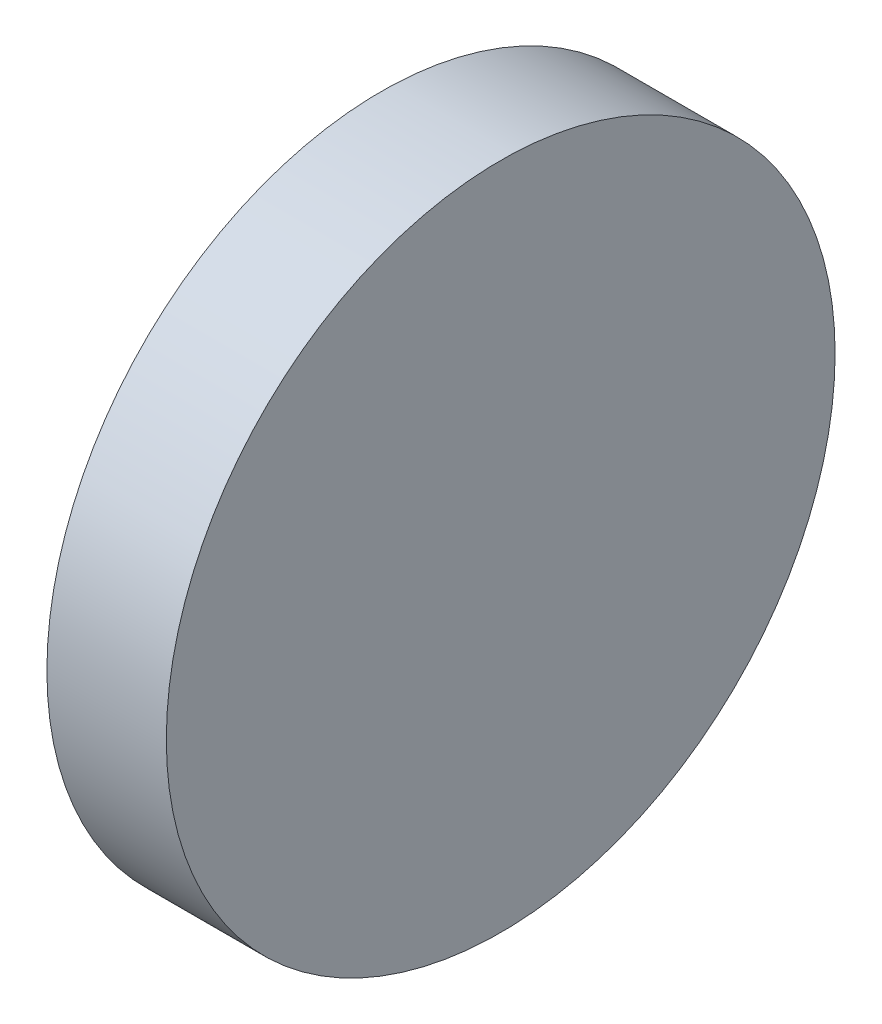
SolidWorks part; units mm, degrees
ref_plane "Front Plane" through (0, 0, 0) normal (0, 0, 1) x (1, 0, 0)
ref_plane "Top Plane" through (0, 0, 0) normal (0, 1, 0) x (1, 0, 0)
ref_plane "Right Plane" through (0, 0, 0) normal (1, 0, 0) x (0, 0, -1)
sketch "Sketch1" plane through (0, 0, 0) normal (1, 0, 0) x (0, 0, -1)
  circle A0 centre (0, 0) radius 7
  dimension "D1" = 14
extrude "Boss-Extrude1" add sketch "Sketch1" along normal blind 2.5
